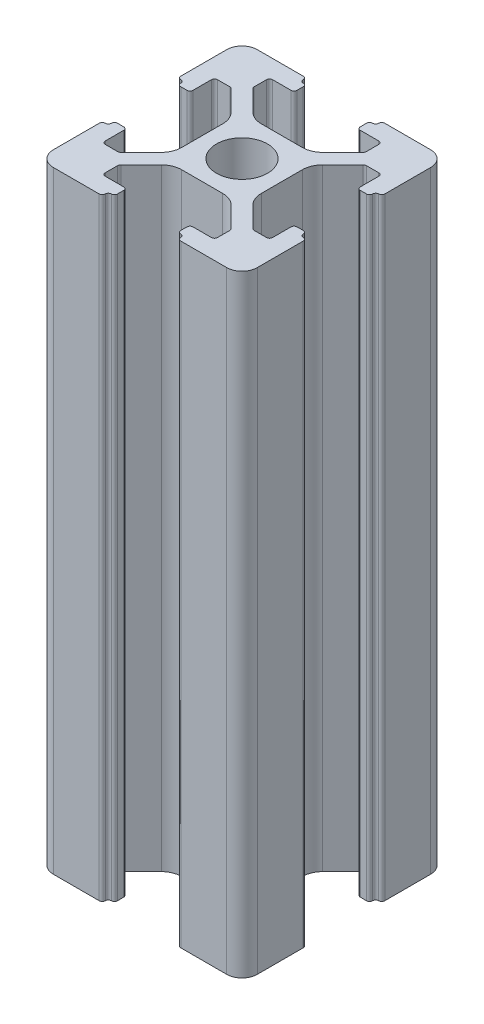
SolidWorks part; units mm, degrees
ref_plane "前视基准面" through (0, 0, 0) normal (0, 0, 1) x (1, 0, 0)
ref_plane "上视基准面" through (0, 0, 0) normal (0, 1, 0) x (1, 0, 0)
ref_plane "右视基准面" through (0, 0, 0) normal (1, 0, 0) x (0, 0, -1)
other "Configuration Table"
sketch "草图1" plane through (0, 0, 0) normal (0, 1, 0) x (1, 0, 0)
  line L0 (-2.5, 0) -> (2.5, 0) construction
  line L1 (10, 8.5) -> (10, 4)
  line L2 (0, 2.5) -> (0, -2.5) construction
  line L3 (10, -8.5) -> (10, -4)
  line L4 (9.1, -3.1) -> (8.5, -3.1)
  line L5 (9.1, 3.1) -> (8.5, 3.1)
  line L6 (8.2, 3.4) -> (8.2, 5.2)
  line L7 (7.9, 5.5) -> (6.6849, 5.5)
  line L8 (6.4728, 5.4121) -> (4.4858, 3.4251)
  line L9 (3.9, 2.0109) -> (3.9, -2.0109)
  line L10 (0, 0) -> (10, 10) construction
  line L11 (8.2, -3.4) -> (8.2, -5.2)
  line L12 (7.9, -5.5) -> (6.6849, -5.5)
  line L13 (6.4728, -5.4121) -> (4.4858, -3.4251)
  line L14 (5.4121, 6.4728) -> (3.4251, 4.4858)
  line L15 (5.5, 7.9) -> (5.5, 6.6849)
  line L16 (3.4, 8.2) -> (5.2, 8.2)
  line L17 (3.1, 9.1) -> (3.1, 8.5)
  line L18 (8.5, 10) -> (4, 10)
  line L19 (-5.4121, 6.4728) -> (-3.4251, 4.4858)
  line L20 (-5.5, 7.9) -> (-5.5, 6.6849)
  line L21 (-3.4, 8.2) -> (-5.2, 8.2)
  line L22 (2.0109, 3.9) -> (-2.0109, 3.9)
  line L23 (-3.1, 9.1) -> (-3.1, 8.5)
  line L24 (-8.5, 10) -> (-4, 10)
  line L25 (-10, 10) -> (0, 0) construction
  line L26 (-10, 8.5) -> (-10, 4)
  line L27 (-9.1, 3.1) -> (-8.5, 3.1)
  line L28 (-3.9, -2.0109) -> (-3.9, 2.0109)
  line L29 (-8.2, 3.4) -> (-8.2, 5.2)
  line L30 (-7.9, 5.5) -> (-6.6849, 5.5)
  line L31 (-6.4728, 5.4121) -> (-4.4858, 3.4251)
  line L32 (-10, -8.5) -> (-10, -4)
  line L33 (-9.1, -3.1) -> (-8.5, -3.1)
  line L34 (-8.2, -3.4) -> (-8.2, -5.2)
  line L35 (-7.9, -5.5) -> (-6.6849, -5.5)
  line L36 (-6.4728, -5.4121) -> (-4.4858, -3.4251)
  line L37 (5.4121, -6.4728) -> (3.4251, -4.4858)
  line L38 (5.5, -7.9) -> (5.5, -6.6849)
  line L39 (3.4, -8.2) -> (5.2, -8.2)
  line L40 (-2.0109, -3.9) -> (2.0109, -3.9)
  line L41 (-5.4121, -6.4728) -> (-3.4251, -4.4858)
  line L42 (-5.5, -7.9) -> (-5.5, -6.6849)
  line L43 (-3.4, -8.2) -> (-5.2, -8.2)
  line L44 (-3.1, -9.1) -> (-3.1, -8.5)
  line L45 (3.1, -9.1) -> (3.1, -8.5)
  line L46 (8.5, -10) -> (4, -10)
  line L47 (-8.5, -10) -> (-4, -10)
  circle A0 centre (0, 0) radius 2.5
  arc A1 (4.4858, 3.4251) -> (3.9, 2.0109) centre (5.9, 2.0109) ccw
  arc A2 (10, 4) -> (9.7, 3.7) centre (9.7, 4) cw
  arc A3 (9.1, 3.1) -> (9.4, 3.4) centre (9.1, 3.4) ccw
  arc A4 (8.5, 3.1) -> (8.2, 3.4) centre (8.5, 3.4) cw
  arc A5 (8.2, 5.2) -> (7.9, 5.5) centre (7.9, 5.2) ccw
  arc A6 (6.6849, 5.5) -> (6.4728, 5.4121) centre (6.6849, 5.2) ccw
  arc A7 (9.4, 3.4) -> (9.7, 3.7) centre (9.7, 3.4) cw
  arc A8 (10, -4) -> (9.7, -3.7) centre (9.7, -4) ccw
  arc A9 (9.4, -3.4) -> (9.7, -3.7) centre (9.7, -3.4) ccw
  arc A10 (9.1, -3.1) -> (9.4, -3.4) centre (9.1, -3.4) cw
  arc A11 (8.5, -3.1) -> (8.2, -3.4) centre (8.5, -3.4) ccw
  arc A12 (8.2, -5.2) -> (7.9, -5.5) centre (7.9, -5.2) cw
  arc A13 (6.6849, -5.5) -> (6.4728, -5.4121) centre (6.6849, -5.2) cw
  arc A14 (4.4858, -3.4251) -> (3.9, -2.0109) centre (5.9, -2.0109) cw
  arc A15 (3.4, 9.4) -> (3.7, 9.7) centre (3.4, 9.7) ccw
  arc A16 (5.5, 6.6849) -> (5.4121, 6.4728) centre (5.2, 6.6849) cw
  arc A17 (5.2, 8.2) -> (5.5, 7.9) centre (5.2, 7.9) cw
  arc A18 (3.1, 8.5) -> (3.4, 8.2) centre (3.4, 8.5) ccw
  arc A19 (3.1, 9.1) -> (3.4, 9.4) centre (3.4, 9.1) cw
  arc A20 (4, 10) -> (3.7, 9.7) centre (4, 9.7) ccw
  arc A21 (-3.4251, 4.4858) -> (-2.0109, 3.9) centre (-2.0109, 5.9) ccw
  arc A22 (-5.5, 6.6849) -> (-5.4121, 6.4728) centre (-5.2, 6.6849) ccw
  arc A23 (-5.2, 8.2) -> (-5.5, 7.9) centre (-5.2, 7.9) ccw
  arc A24 (-3.1, 8.5) -> (-3.4, 8.2) centre (-3.4, 8.5) cw
  arc A25 (-3.1, 9.1) -> (-3.4, 9.4) centre (-3.4, 9.1) ccw
  arc A26 (-3.4, 9.4) -> (-3.7, 9.7) centre (-3.4, 9.7) cw
  arc A27 (-4, 10) -> (-3.7, 9.7) centre (-4, 9.7) cw
  arc A28 (3.4251, 4.4858) -> (2.0109, 3.9) centre (2.0109, 5.9) cw
  arc A29 (-4.4858, -3.4251) -> (-3.9, -2.0109) centre (-5.9, -2.0109) ccw
  arc A30 (-10, 4) -> (-9.7, 3.7) centre (-9.7, 4) ccw
  arc A31 (-9.4, 3.4) -> (-9.7, 3.7) centre (-9.7, 3.4) ccw
  arc A32 (-9.1, 3.1) -> (-9.4, 3.4) centre (-9.1, 3.4) cw
  arc A33 (-8.5, 3.1) -> (-8.2, 3.4) centre (-8.5, 3.4) ccw
  arc A34 (-8.2, 5.2) -> (-7.9, 5.5) centre (-7.9, 5.2) cw
  arc A35 (-6.6849, 5.5) -> (-6.4728, 5.4121) centre (-6.6849, 5.2) cw
  arc A36 (-4.4858, 3.4251) -> (-3.9, 2.0109) centre (-5.9, 2.0109) cw
  arc A37 (-10, -4) -> (-9.7, -3.7) centre (-9.7, -4) cw
  arc A38 (-9.1, -3.1) -> (-9.4, -3.4) centre (-9.1, -3.4) ccw
  arc A39 (-8.5, -3.1) -> (-8.2, -3.4) centre (-8.5, -3.4) cw
  arc A40 (-8.2, -5.2) -> (-7.9, -5.5) centre (-7.9, -5.2) ccw
  arc A41 (-6.6849, -5.5) -> (-6.4728, -5.4121) centre (-6.6849, -5.2) ccw
  arc A42 (-9.4, -3.4) -> (-9.7, -3.7) centre (-9.7, -3.4) cw
  arc A43 (3.4251, -4.4858) -> (2.0109, -3.9) centre (2.0109, -5.9) ccw
  arc A44 (5.5, -6.6849) -> (5.4121, -6.4728) centre (5.2, -6.6849) ccw
  arc A45 (5.2, -8.2) -> (5.5, -7.9) centre (5.2, -7.9) ccw
  arc A46 (3.1, -8.5) -> (3.4, -8.2) centre (3.4, -8.5) cw
  arc A47 (3.1, -9.1) -> (3.4, -9.4) centre (3.4, -9.1) ccw
  arc A48 (3.4, -9.4) -> (3.7, -9.7) centre (3.4, -9.7) cw
  arc A49 (4, -10) -> (3.7, -9.7) centre (4, -9.7) cw
  arc A50 (-3.4, -9.4) -> (-3.7, -9.7) centre (-3.4, -9.7) ccw
  arc A51 (-5.5, -6.6849) -> (-5.4121, -6.4728) centre (-5.2, -6.6849) cw
  arc A52 (-5.2, -8.2) -> (-5.5, -7.9) centre (-5.2, -7.9) cw
  arc A53 (-3.1, -8.5) -> (-3.4, -8.2) centre (-3.4, -8.5) ccw
  arc A54 (-3.1, -9.1) -> (-3.4, -9.4) centre (-3.4, -9.1) cw
  arc A55 (-4, -10) -> (-3.7, -9.7) centre (-4, -9.7) ccw
  arc A56 (-3.4251, -4.4858) -> (-2.0109, -3.9) centre (-2.0109, -5.9) cw
  arc A57 (-10, -8.5) -> (-8.5, -10) centre (-8.5, -8.5) ccw
  arc A58 (8.5, -10) -> (10, -8.5) centre (8.5, -8.5) ccw
  arc A59 (10, 8.5) -> (8.5, 10) centre (8.5, 8.5) ccw
  arc A60 (-10, 8.5) -> (-8.5, 10) centre (-8.5, 8.5) cw
  point P47 (3.9, 0)
  point P86 (0, 3.9)
  point P164 (-3.9, 0)
  point P165 (0, -3.9)
  dimension "D1" = 5
extrude "凸台-拉伸1" add sketch "草图1" along normal blind 60
